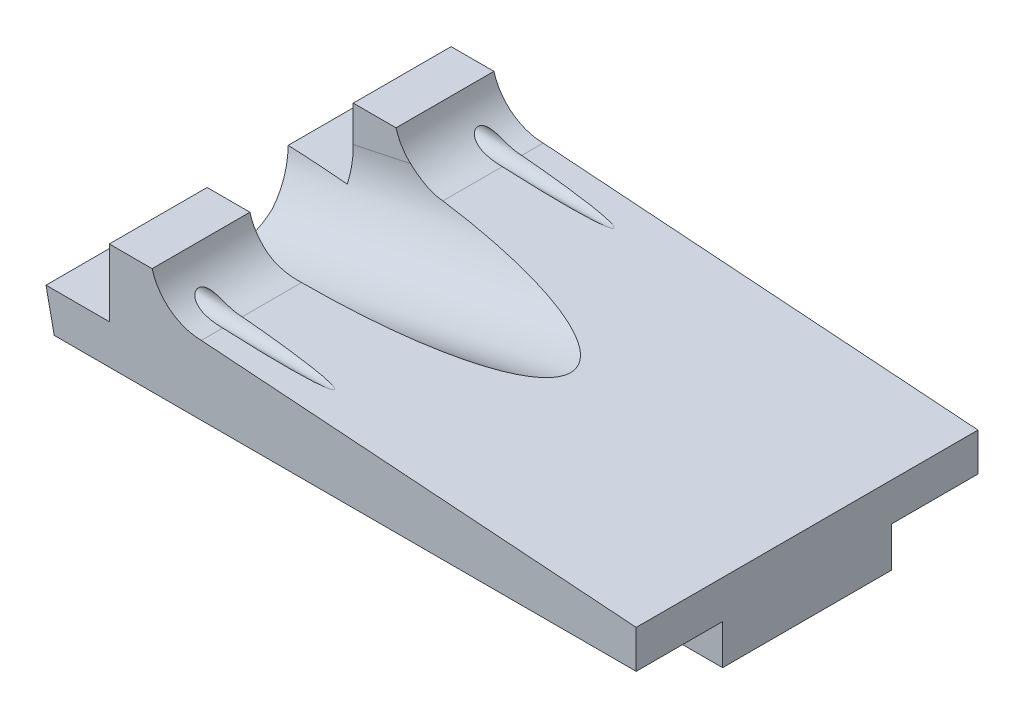
SolidWorks part; units mm, degrees
ref_plane "Front Plane" through (0, 0, 0) normal (0, 0, 1) x (1, 0, 0)
ref_plane "Top Plane" through (0, 0, 0) normal (0, 1, 0) x (1, 0, 0)
ref_plane "Right Plane" through (0, 0, 0) normal (1, 0, 0) x (0, 0, -1)
sketch "Sketch1" plane through (0, 0, 0) normal (0, 1, 0) x (1, 0, 0)
  line L1 (0, 0) -> (91.6, 0)
  line L2 (0, 0) -> (0, 26.6)
  line L3 (0, 26.6) -> (91.6, 26.6)
  line L4 (91.6, 0) -> (91.6, 26.6)
  dimension "D1" = 91.6
  dimension "D2" = 26.6
extrude "Boss-Extrude1" add sketch "Sketch1" along normal blind 6.3
sketch "Sketch2" plane through (0, 6.3, 0) normal (0, 1, 0) x (1, 0, 0)
  line L0 (0, 0) -> (91.6, 0) construction
  line L1 (0, 40.2) -> (91.6, 40.2)
  line L2 (0, 40.2) -> (0, -13.6)
  line L3 (0, -13.6) -> (91.6, -13.6)
  line L4 (91.6, 40.2) -> (91.6, -13.6)
  dimension "D1" = 53.8
  dimension "D2" = 13.6
  dimension "D3" = 91.6
  dimension "D4" = 13.6
extrude "Boss-Extrude2" add sketch "Sketch2" along normal blind 6
sketch "Sketch3" plane through (0, 0, 13.6) normal (0, 0, 1) x (1, 0, 0)
  line L0 (91.6, 12.3) -> (23.1556, 17.1956)
  line L3 (0, 12.3) -> (91.6, 12.3)
  line L4 (0, 6.3) -> (-4, 25.4)
  line L5 (-4, 25.4) -> (15.1, 25.4)
  line L6 (0, 0) -> (91.6, 0) construction
  line L7 (0, 12.3) -> (0, 6.3)
  arc A0 (15.1, 25.4) -> (23.1556, 17.1956) centre (23.1993, 25.2954) ccw
  dimension "D5" = 4.8956
  dimension "D1" = 8.1
  dimension "D2" = 68.4444
  dimension "D3" = 25.4
  dimension "D4" = 4
  dimension "D6" = 19.9905
extrude "Boss-Extrude3" add sketch "Sketch3" against normal up to surface (53.8 mm away) up to face at (45.8, 9.3, -40.2)
sketch "Sketch5" plane through (1.2639, 0.2647, 0) normal (-0.9788, -0.205, 0) x (0, 0, 1)
  line L0 (-26.6, 0) -> (0, 0) construction
  line L1 (-40.2, 6.1662) -> (-40.2, 25.6806) construction
  circle A0 centre (-13.3, 15) radius 11.5
  dimension "D1" = 23
  dimension "D2" = 15
  dimension "D3" = 26.9
extrude "Cut-Extrude1" cut sketch "Sketch5" against normal mid plane 113
sketch "Sketch6" plane through (1.2639, 0.2647, 0) normal (-0.9788, -0.205, 0) x (0, 0, 1)
  line L0 (-9.0368, 25.6806) -> (13.6, 25.6806) construction
  line L1 (-24.7956, 14.6806) -> (-1.7956, 14.6806)
  line L2 (-24.7956, 14.6806) -> (-24.7956, 25.6806)
  line L3 (-24.7956, 25.6806) -> (-1.7956, 25.6806)
  line L4 (-1.7956, 14.6806) -> (-1.7956, 25.6806)
  arc A0 (-17.5632, 25.6806) -> (-20.6631, 6.1662) centre (-13.3, 15) ccw construction
  dimension "D1" = 23
  dimension "D2" = 11
extrude "Cut-Extrude2" cut sketch "Sketch6" against normal mid plane 80
sketch "Sketch8" plane through (0, 0, 0) normal (0, -1, 0) x (1, 0, 0)
  line L0 (91.6, 0) -> (91.6, -26.6) construction
  line L1 (0, -26.6) -> (0, 0) construction
  circle A0 centre (15.8, -4.3) radius 1.6
  circle A1 centre (85.8, -4.3) radius 1.6
  circle A2 centre (85.8, -22.3) radius 1.6
  circle A3 centre (15.8, -22.3) radius 1.6
  point P12 (0, -13.3)
  point P13 (91.6, -13.3)
  dimension "D1" = 3.2
  dimension "D2" = 3.2
  dimension "D3" = 3.2
  dimension "D4" = 3.2
  dimension "D5" = 18
  dimension "D6" = 18
  dimension "D7" = 5.8
  dimension "D8" = 70
  dimension "D9" = 9
  dimension "D10" = 9
  dimension "D11" = 9
  dimension "D12" = 9
extrude "Cut-Extrude3" cut sketch "Sketch8" against normal blind 6
cosmetic thread "Cosmetic Thread1" parameters "D1"=6, "D2"=4
cosmetic thread "Cosmetic Thread2" parameters "D1"=6, "D2"=4
cosmetic thread "Cosmetic Thread3" parameters "D1"=6, "D2"=4
cosmetic thread "Cosmetic Thread4" parameters "D1"=6, "D2"=4
sketch "Sketch9" plane through (0, 0, 13.6) normal (0, 0, 1) x (1, 0, 0)
  line L3 (-1.2984, 12.5) -> (6.3667, 12.5)
  line L4 (6.3667, 23.1) -> (6.3667, 12.5)
  line L5 (-4, 25.4) -> (0, 6.3)
  line L6 (0, 6.3) -> (91.6, 6.3)
  line L7 (91.6, 6.3) -> (91.6, 12.3)
  line L8 (91.6, 12.3) -> (23.1556, 17.1956)
  line L9 (15.1, 25.4) -> (-4, 25.4)
  line L10 (-4, 25.4) -> (-1.2984, 12.5)
  line L14 (15.1, 25.4) -> (-4, 25.4)
  line L16 (6.3667, 23.1) -> (15.4025, 23.1)
  arc A1 (15.1, 25.4) -> (23.1556, 17.1956) centre (23.1993, 25.2954) ccw
  arc A2 (15.1, 25.4) -> (15.4025, 23.1) centre (23.1993, 25.2954) ccw
  dimension "D3" = 2.3
  dimension "D4" = 10.3667
  dimension "D1" = 0
extrude "Cut-Extrude4" cut sketch "Sketch9" against normal up to surface (53.8 mm away) up to face at (35.9579, 15.203, -40.2)
sketch "Sketch10" plane through (6.3667, 0, 0) normal (-1, 0, 0) x (0, 0, 1)
  line L1 (13.6, 12.5) -> (-40.2, 12.5)
  line L2 (13.6, 12.5) -> (13.6, 23.1)
  line L3 (13.6, 23.1) -> (-40.2, 23.1)
  line L4 (-40.2, 12.5) -> (-40.2, 23.1)
extrude "Cut-Extrude5" cut sketch "Sketch10" against normal blind 2.3
sketch "Sketch11" plane through (8.6667, 0, 0) normal (-1, 0, 0) x (0, 0, 1)
  line L0 (13.6, 23.1) -> (-1.7956, 23.1) construction
  line L1 (-24.7956, 23.1) -> (-40.2, 23.1) construction
  line L2 (13.6, 12.5) -> (13.6, 23.1) construction
  circle A0 centre (-35.3, 17.65) radius 1.6
  circle A1 centre (8.7, 17.65) radius 1.6
  dimension "D1" = 3.2
  dimension "D2" = 3.2
  dimension "D3" = 44
  dimension "D4" = 5.45
  dimension "D5" = 5.45
  dimension "D6" = 4.9
extrude "Cut-Extrude6" cut sketch "Sketch11" against normal up to surface (82.9343 mm away)
